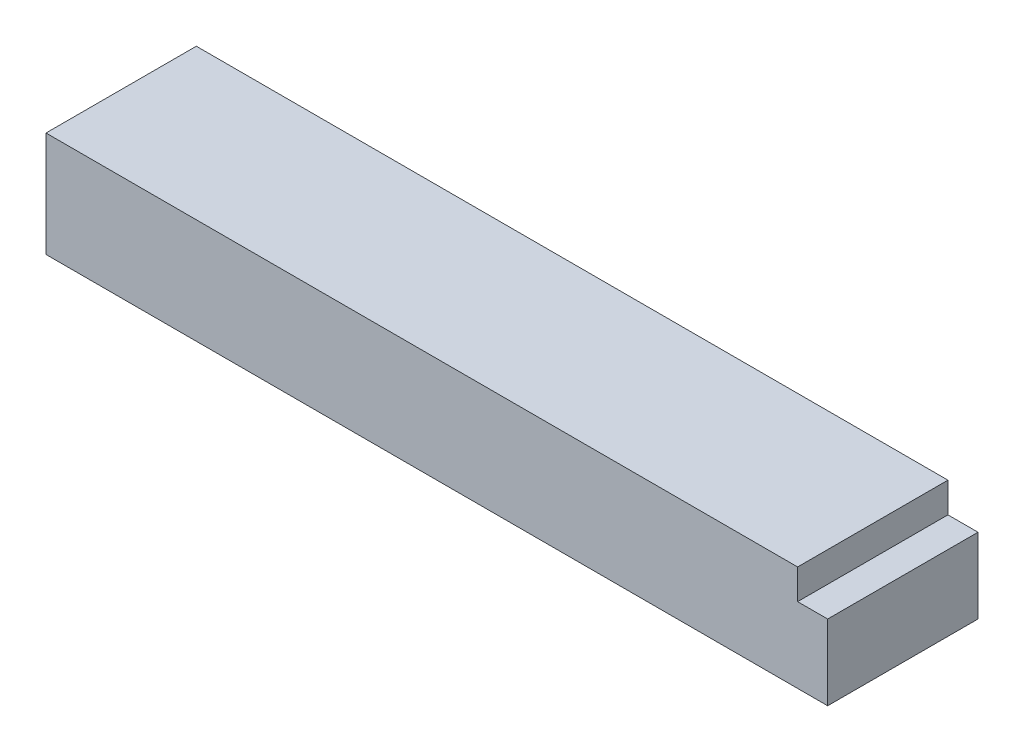
SolidWorks part; units mm, degrees
material "Beech"
ref_plane "Front Plane" through (0, 0, 0) normal (0, 0, 1) x (1, 0, 0)
ref_plane "Top Plane" through (0, 0, 0) normal (0, 1, 0) x (1, 0, 0)
ref_plane "Right Plane" through (0, 0, 0) normal (1, 0, 0) x (0, 0, -1)
sketch "Sketch1" plane through (0, 0, 0) normal (0, 0, 1) x (1, 0, 0)
  line L0 (-89.8621, 8.3966) -> (-89.8621, -5.6034)
  line L1 (-89.8621, -5.6034) -> (14.1379, -5.6034)
  line L2 (14.1379, -5.6034) -> (14.1379, 4.3966)
  line L3 (14.1379, 4.3966) -> (10.1379, 4.3966)
  line L4 (10.1379, 4.3966) -> (10.1379, 8.3966)
  line L5 (10.1379, 8.3966) -> (-89.8621, 8.3966)
  point P2 (0, 0)
  dimension "D1" = 10
  dimension "D2" = 4
  dimension "D3" = 104
  dimension "D4" = 4
extrude "Boss-Extrude1" add sketch "Sketch1" along normal blind 20
